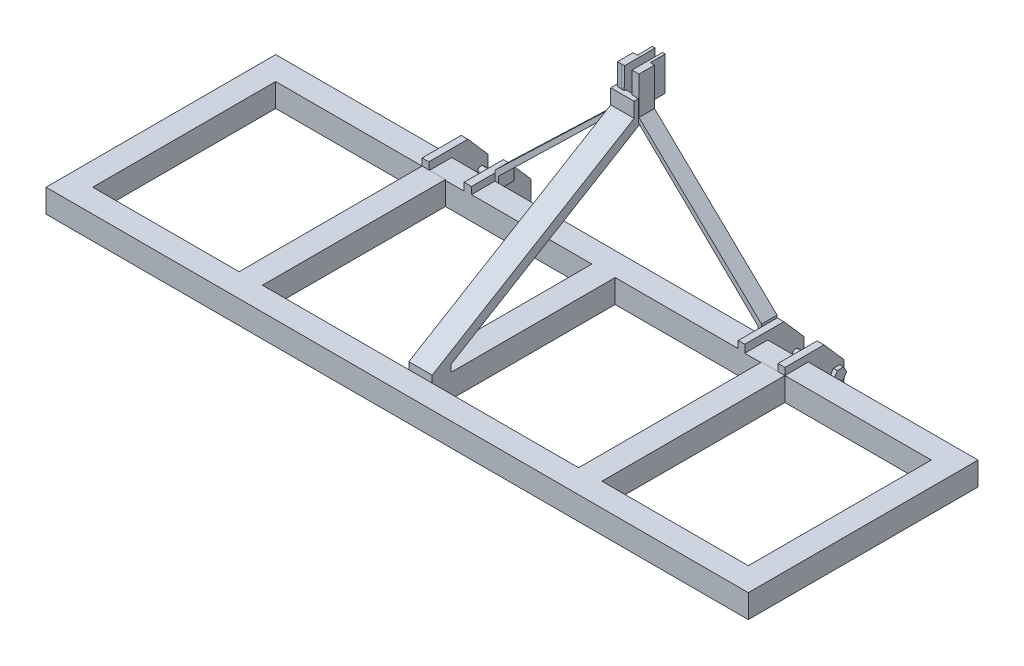
SolidWorks part; units mm, degrees
ref_plane "Ön Düzlem" through (0, 0, 0) normal (0, 0, 1) x (1, 0, 0)
ref_plane "Üst Düzlem" through (0, 0, 0) normal (0, 1, 0) x (1, 0, 0)
ref_plane "Sağ Düzlem" through (0, 0, 0) normal (1, 0, 0) x (0, 0, -1)
sketch "Sketch1" plane through (0, 0, 0) normal (0, 1, 0) x (1, 0, 0)
  line L0 (-163.1156, 16.6804) -> (-163.1156, -40.6142)
  line L1 (-157.1156, 10.6804) -> (-119.502, 10.6804)
  line L2 (-157.1156, 10.6804) -> (-157.1156, -36.3366)
  line L3 (-157.1156, -36.3366) -> (-119.502, -36.3366)
  line L4 (-119.502, 10.6804) -> (-119.502, -36.3366)
  line L5 (-113.502, 10.6804) -> (-75.8884, 10.6804)
  line L6 (-113.502, 10.6804) -> (-113.502, -36.3366)
  line L7 (-113.502, -36.3366) -> (-75.8884, -36.3366)
  line L8 (-75.8884, 10.6804) -> (-75.8884, -36.3366)
  line L9 (-69.8884, 10.6804) -> (-32.2748, 10.6804)
  line L10 (-69.8884, 10.6804) -> (-69.8884, -36.3366)
  line L11 (-69.8884, -36.3366) -> (-32.2748, -36.3366)
  line L12 (-32.2748, 10.6804) -> (-32.2748, -36.3366)
  line L13 (-26.2748, 10.6804) -> (11.3388, 10.6804)
  line L14 (-26.2748, 10.6804) -> (-26.2748, -36.3366)
  line L15 (-26.2748, -36.3366) -> (11.3388, -36.3366)
  line L16 (11.3388, 10.6804) -> (11.3388, -36.3366)
  line L17 (-163.1156, 16.6804) -> (16.4823, 16.6804)
  line L19 (-163.1156, -40.6142) -> (-163.1156, -42.3366)
  line L21 (-163.1156, -42.3366) -> (17.3388, -42.3366)
  line L22 (17.3388, -42.3366) -> (17.3388, 16.6804)
  line L23 (17.3388, 16.6804) -> (16.4823, 16.6804)
  dimension "D1" = 6
  dimension "D2" = 6
  dimension "D3" = 6
  dimension "D4" = 6
  dimension "D5" = 6
extrude "Boss-Extrude1" add sketch "Sketch1" along normal blind 6
ref_plane "Plane1" through (-119.502, 0, 0) normal (-1, 0, 0) x (0, 0, 1)
sketch "Sketch2" plane through (-119.502, 0, 0) normal (-1, 0, 0) x (0, 0, 1)
  line L0 (-10.6804, 6) -> (-10.6804, 7.807)
  line L1 (-10.6804, 7.807) -> (-20.7374, 7.807)
  line L2 (-20.7374, 7.807) -> (-25.9258, 1.8721)
  line L3 (-25.9258, 1.8721) -> (-25.9258, -3.0739)
  line L4 (-16.6804, 0) -> (-20.7374, 0)
  line L5 (-20.7374, 0) -> (-25.9258, -6.2006)
  line L6 (-25.9258, -6.2006) -> (-25.9258, -3.0739)
  line L7 (-16.6804, 0) -> (-10.6804, 0)
  line L8 (-10.6804, 0) -> (-10.6804, 6)
extrude "Boss-Extrude2" add sketch "Sketch2" against normal blind 6
mirror "Mirror2" about plane through (-75.8884, 6, -10.6804) normal (-1, 0, 0) of "Boss-Extrude2"
mirror "Mirror3" about plane through (-32.2748, 0, 0) normal (1, 0, 0) of "Mirror2"
mirror "Mirror4" about plane through (-113.502, 0, 0) normal (-1, 0, 0) of "Boss-Extrude2"
sketch "Sketch6" plane through (0, 7.807, 0) normal (0, 1, 0) x (1, 0, 0)
  line L0 (-28.0544, 10.6804) -> (-28.0544, 26.5012)
  line L1 (-38.2748, 10.6804) -> (-26.2748, 10.6804) construction
  line L2 (-28.0544, 26.5012) -> (-36.5878, 26.5012)
  line L3 (-36.5878, 26.5012) -> (-36.5878, 10.6804)
  line L4 (-36.5878, 10.6804) -> (-28.0544, 10.6804)
extrude "Cut-Extrude2" cut sketch "Sketch6" against normal blind 2
sketch "Sketch7" plane through (0, 5.807, 0) normal (0, 1, 0) x (1, 0, 0)
  line L0 (-28.0544, 16.5831) -> (-36.5878, 16.5831)
  line L1 (-28.0544, 10.6804) -> (-28.0544, 22.4858) construction
  line L2 (-36.5878, 22.4858) -> (-36.5878, 10.6804) construction
  line L3 (-36.5878, 16.5831) -> (-36.5878, 27.4839)
  line L4 (-36.5878, 27.4839) -> (-28.0544, 27.4839)
  line L5 (-28.0544, 27.4839) -> (-28.0544, 16.5831)
extrude "Cut-Extrude3" cut sketch "Sketch7" against normal blind 16
sketch "Sketch8" plane through (0, 0, -16.6804) normal (0, 0, -1) x (-1, 0, 0)
  line L0 (38.2748, 4.5223) -> (38.2748, 8.4501)
  line L1 (38.2748, 0) -> (38.2748, 6) construction
  line L2 (38.2748, 8.4501) -> (69.7727, 38.6666)
  line L4 (69.7727, 37.2783) -> (39.1581, 7.5294)
  line L5 (39.1581, 7.5294) -> (39.1581, 4.5223)
  line L6 (39.1581, 4.5223) -> (38.2748, 4.5223)
  line L8 (69.7727, 48.3347) -> (70.874, 48.3347)
  line L9 (70.874, 48.3347) -> (70.874, 37.2783)
  line L10 (70.874, 37.2783) -> (69.7727, 37.2783)
  line L11 (69.7727, 38.6666) -> (69.7727, 48.3347)
extrude "Boss-Extrude6" add sketch "Sketch8" along normal blind 4
sketch "Sketch9" plane through (0, 7.807, 0) normal (0, 1, 0) x (1, 0, 0)
  line L0 (-108.6991, 10.6804) -> (-108.6991, 27.5716)
  line L1 (-107.502, 10.6804) -> (-119.502, 10.6804) construction
  line L2 (-108.6991, 27.5716) -> (-118.4833, 27.5716)
  line L3 (-118.4833, 27.5716) -> (-118.4833, 10.6804)
  line L4 (-118.4833, 10.6804) -> (-108.6991, 10.6804)
extrude "Cut-Extrude4" cut sketch "Sketch9" against normal blind 2
sketch "Sketch10" plane through (0, 5.807, 0) normal (0, 1, 0) x (1, 0, 0)
  line L0 (-108.6991, 16.5831) -> (-118.4833, 16.5831)
  line L1 (-108.6991, 10.6804) -> (-108.6991, 22.4858) construction
  line L2 (-118.4833, 22.4858) -> (-118.4833, 10.6804) construction
  line L3 (-118.4833, 16.5831) -> (-118.4833, 27.6128)
  line L4 (-118.4833, 27.6128) -> (-108.6991, 27.6128)
  line L5 (-108.6991, 27.6128) -> (-108.6991, 16.5831)
extrude "Cut-Extrude5" cut sketch "Sketch10" against normal blind 15
sketch "Sketch11" plane through (0, 6, 0) normal (0, 1, 0) x (1, 0, 0)
  line L0 (-72.5334, 16.6804) -> (-72.5334, 9.7603)
  line L1 (-39.1581, 16.6804) -> (-107.502, 16.6804) construction
ref_plane "Plane10" through (-72.5334, 0, 0) normal (1, 0, 0) x (0, 0, -1)
mirror "Mirror7" about plane through (-72.5334, 0, 0) normal (1, 0, 0) of "Boss-Extrude6"
sketch "Sketch12" plane through (-107.502, 0, 0) normal (1, 0, 0) x (0, 0, -1)
  line L0 (16.6804, 0) -> (20.7374, 0)
  line L1 (20.7374, 0) -> (25.9258, -6.2006)
  line L2 (25.9258, -6.2006) -> (25.9258, 1.8721)
  line L3 (25.9258, 1.8721) -> (20.7374, 7.807)
  line L4 (20.7374, 7.807) -> (10.6804, 7.807)
  line L5 (10.6804, 7.807) -> (10.6804, 6)
  line L6 (10.6804, 6) -> (16.6804, 6)
  line L7 (16.6804, 6) -> (16.6804, -0.0906)
extrude "Boss-Extrude8" add sketch "Sketch12" along normal blind 0.7 contours L7 L0 L1 L2 L3 L4 L5
sketch "Sketch14" plane through (-118.4833, 0, 0) normal (1, 0, 0) x (0, 0, -1)
  line L0 (16.5831, 0) -> (16.5831, 5.807)
  line L1 (16.5831, 5.807) -> (10.6804, 5.807)
  line L2 (16.5831, 5.807) -> (10.6804, 5.807) construction
  line L3 (10.6804, 5.807) -> (10.6804, 7.807)
  line L4 (10.6804, 7.807) -> (20.7374, 7.807)
  line L5 (20.7374, 7.807) -> (25.9258, 1.8721)
  line L6 (25.9258, 1.8721) -> (25.9258, -6.2006)
  line L7 (25.9258, -6.2006) -> (20.7374, 0)
  line L8 (20.7374, 0) -> (16.5831, 0)
extrude "Boss-Extrude9" add sketch "Sketch14" along normal blind 0.7
sketch "Sketch15" plane through (-70.874, 0, 0) normal (-1, 0, 0) x (0, 0, 1)
  line L0 (-16.6804, 48.3347) -> (-16.6804, 39.5696)
  line L1 (-16.6804, 37.2783) -> (-16.6804, 48.3347) construction
  line L2 (-16.6804, 39.5696) -> (-24.5226, 39.5696)
  line L3 (-24.5226, 39.5696) -> (-24.5226, 48.3347)
  line L4 (-24.5226, 48.3347) -> (-16.6804, 48.3347)
extrude "Boss-Extrude11" add sketch "Sketch15" along normal blind 0.7
sketch "Sketch19" plane through (-74.1928, 0, 0) normal (1, 0, 0) x (0, 0, -1)
  line L0 (20.6804, 48.3347) -> (20.7548, 39.7929)
  line L1 (20.7548, 39.7929) -> (16.5668, 39.7929)
  line L2 (16.5668, 39.7929) -> (16.6804, 48.3347)
  line L3 (16.6804, 48.3347) -> (20.6804, 48.3347)
extrude "Boss-Extrude12" add sketch "Sketch19" along normal blind 0.7
sketch "Sketch21" plane through (-74.1928, 0, 0) normal (1, 0, 0) x (0, 0, -1)
  line L0 (20.7548, 39.7929) -> (24.5375, 39.7929)
  line L1 (24.5375, 39.7929) -> (24.5375, 48.363)
  line L2 (24.5375, 48.363) -> (20.6804, 48.3347)
  line L3 (20.7548, 39.7929) -> (20.6804, 48.3347) construction
  line L4 (20.6804, 39.7929) -> (20.6804, 48.3347) construction
  line L5 (20.6804, 48.3347) -> (20.7548, 39.7929)
extrude "Boss-Extrude13" add sketch "Sketch21" along normal blind 0.7
sketch "Sketch23" plane through (-75.8884, 0, 0) normal (-1, 0, 0) x (0, 0, 1)
  line L0 (36.3366, 6) -> (36.3366, 7.7949)
  line L1 (36.3366, 7.7949) -> (-15.5417, 38.987)
  line L2 (-15.5417, 38.987) -> (-15.5417, 42.8014)
  line L3 (-15.5417, 42.8014) -> (-17.0173, 42.8014)
  line L4 (-17.0173, 42.8014) -> (-17.0173, 38.3354)
  line L5 (-17.0173, 38.3354) -> (-17.0173, 36.9552)
  line L6 (-17.0173, 36.9552) -> (31.4919, 7.7949)
  line L7 (31.4919, 7.7949) -> (31.4919, 4.6887)
  line L8 (31.4919, 4.6887) -> (36.3366, 4.6887)
  line L9 (36.3366, 6) -> (36.3366, 0) construction
  line L10 (36.3366, 4.6887) -> (36.3366, 6)
extrude "Boss-Extrude15" add sketch "Sketch23" against normal blind 6
sketch "Sketch24" plane through (-119.502, 0, 0) normal (-1, 0, 0) x (0, 0, 1)
  line L1 (-22.2782, -0.491) -> (-23.0544, 0.8534)
  line L2 (-23.0544, 0.8534) -> (-24.6068, 0.8534)
  line L3 (-24.6068, 0.8534) -> (-25.383, -0.491)
  line L4 (-25.383, -0.491) -> (-24.6068, -1.8354)
  line L5 (-24.6068, -1.8354) -> (-23.0544, -1.8354)
  line L6 (-23.0544, -1.8354) -> (-22.2782, -0.491)
  circle A0 centre (-23.8306, -0.491) radius 1.3444 construction
extrude "Boss-Extrude16" add sketch "Sketch24" along normal blind 1
sketch "Sketch25" plane through (-106.802, 0, 0) normal (1, 0, 0) x (0, 0, -1)
  circle A0 centre (24.0598, -0.5719) radius 0.7856
extrude "Boss-Extrude17" add sketch "Sketch25" against normal blind 13
sketch "Sketch26" plane through (-26.2748, 0, 0) normal (1, 0, 0) x (0, 0, -1)
  line L1 (25.5384, 0) -> (24.7366, 1.3887)
  line L2 (24.7366, 1.3887) -> (23.133, 1.3887)
  line L3 (23.133, 1.3887) -> (22.3312, 0)
  line L4 (22.3312, 0) -> (23.133, -1.3887)
  line L5 (23.133, -1.3887) -> (24.7366, -1.3887)
  line L6 (24.7366, -1.3887) -> (25.5384, 0)
  circle A0 centre (23.9348, 0) radius 1.3887 construction
extrude "Boss-Extrude18" add sketch "Sketch26" along normal blind 1
sketch "Sketch27" plane through (-38.2748, 0, 0) normal (-1, 0, 0) x (0, 0, 1)
  circle A0 centre (-23.7479, -0.5287) radius 0.8136
extrude "Boss-Extrude19" add sketch "Sketch27" against normal blind 12
